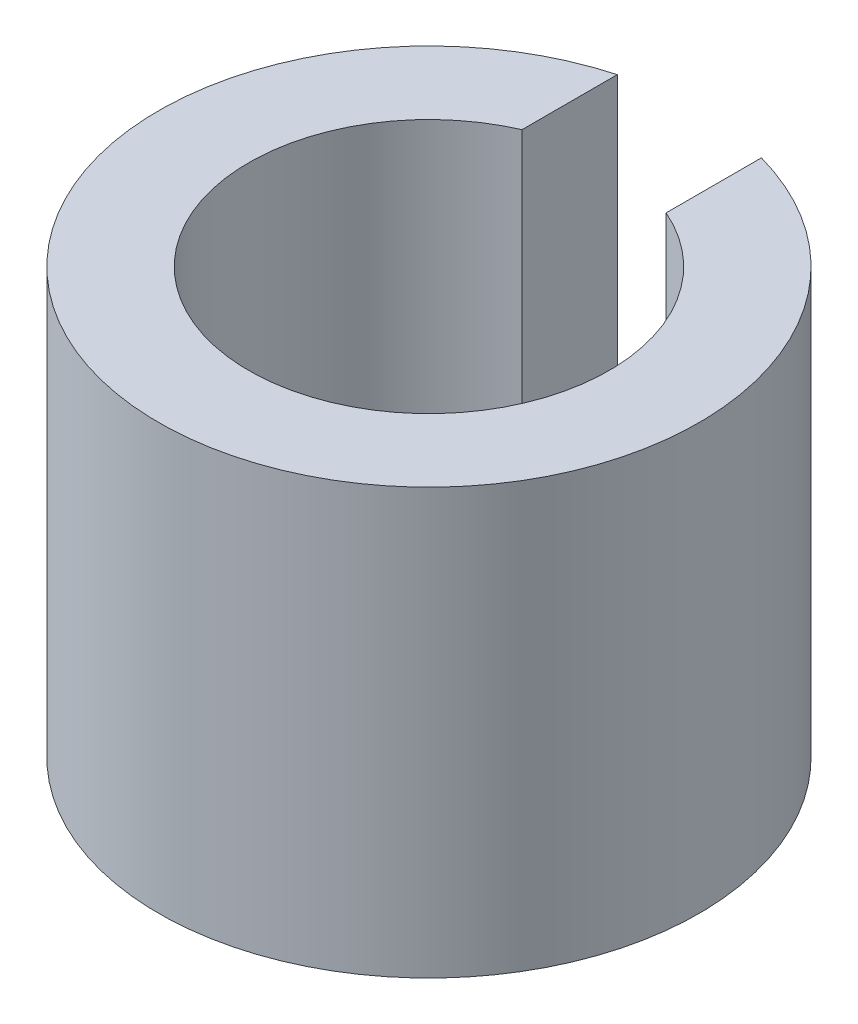
SolidWorks part; units mm, degrees
material "Plain Carbon Steel"
ref_plane "Front Plane" through (0, 0, 0) normal (0, 0, 1) x (1, 0, 0)
ref_plane "Top Plane" through (0, 0, 0) normal (0, 1, 0) x (1, 0, 0)
ref_plane "Right Plane" through (0, 0, 0) normal (1, 0, 0) x (0, 0, -1)
sketch "Sketch1" plane through (0, 0, 0) normal (0, 1, 0) x (1, 0, 0)
  circle A0 centre (0, 0) radius 7.5
  circle A1 centre (0, 0) radius 5
  dimension "D1" = 15
  dimension "D2" = 10
extrude "Boss-Extrude1" add sketch "Sketch1" along normal blind 11.8
sketch "Sketch2" plane through (0, 11.8, 0) normal (0, 1, 0) x (1, 0, 0)
  line L0 (-2, 7.9423) -> (-2, 3.9423)
  line L1 (-2, 7.9423) -> (2, 7.9423)
  line L2 (-2, 3.9423) -> (2, 3.9423)
  line L3 (2, 7.9423) -> (2, 3.9423)
  line L4 (-2, 7.9423) -> (2, 3.9423) construction
  line L5 (-2, 3.9423) -> (2, 7.9423) construction
  line L6 (0, 5.9423) -> (0, 0) construction
  point P1 (0, 5.9423)
  dimension "D1" = 4
extrude "Cut-Extrude1" cut sketch "Sketch2" against normal through all
